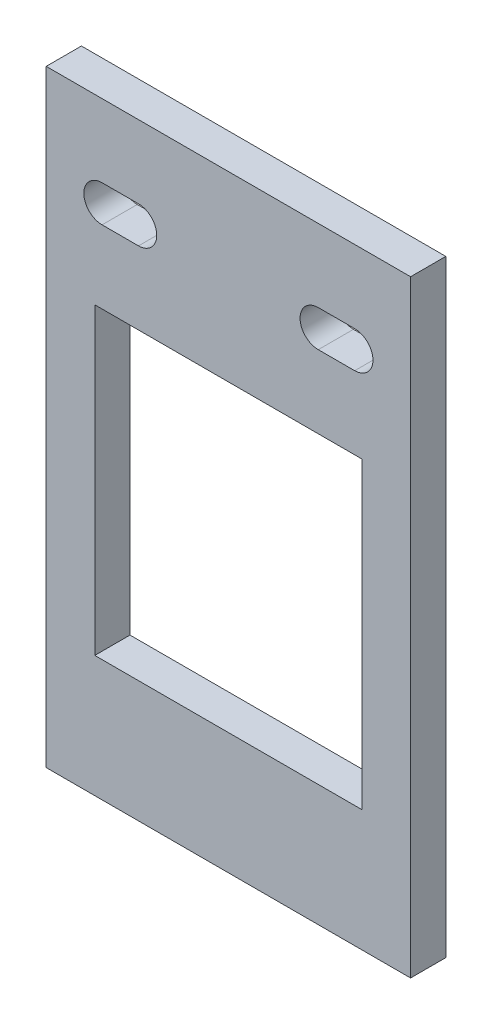
SolidWorks part; units mm, degrees
ref_plane "Front Plane" through (0, 0, 0) normal (0, 0, 1) x (1, 0, 0)
ref_plane "Top Plane" through (0, 0, 0) normal (0, 1, 0) x (1, 0, 0)
ref_plane "Right Plane" through (0, 0, 0) normal (1, 0, 0) x (0, 0, -1)
sketch "Sketch1" plane through (0, 0, 0) normal (0, 0, 1) x (1, 0, 0)
  line L0 (0, 42.5) -> (30, 42.5) construction
  line L1 (0, 0) -> (30, 0)
  line L2 (0, 0) -> (0, 50)
  line L3 (0, 50) -> (30, 50)
  line L4 (30, 0) -> (30, 50)
  line L5 (15, 50) -> (15, 0) construction
  line L6 (4.6, 44) -> (7.6, 44)
  line L7 (4.6, 41) -> (7.6, 41)
  line L8 (25.4, 44) -> (22.4, 44)
  line L9 (25.4, 41) -> (22.4, 41)
  line L11 (26, 10) -> (4, 10)
  line L12 (26, 10) -> (26, 35)
  line L13 (26, 35) -> (4, 35)
  line L14 (4, 10) -> (4, 35)
  line L15 (26, 10) -> (4, 35) construction
  line L16 (26, 35) -> (4, 10) construction
  circle A0 centre (6.1, 42.5) radius 1.5 construction
  circle A1 centre (23.9, 42.5) radius 1.5 construction
  arc A2 (4.6, 44) -> (4.6, 41) centre (4.6, 42.5) ccw
  arc A3 (7.6, 41) -> (7.6, 44) centre (7.6, 42.5) ccw
  arc A4 (22.4, 41) -> (22.4, 44) centre (22.4, 42.5) cw
  arc A5 (25.4, 44) -> (25.4, 41) centre (25.4, 42.5) cw
  point P25 (15, 22.5)
  dimension "D4" = 3
  dimension "D5" = 17.8
  dimension "D1" = 30
  dimension "D2" = 50
  dimension "D3" = 7.5
  dimension "D6" = 7.5
  dimension "D7" = 25
  dimension "D8" = 22
extrude "Boss-Extrude1" add sketch "Sketch1" along normal mid plane 2.9
